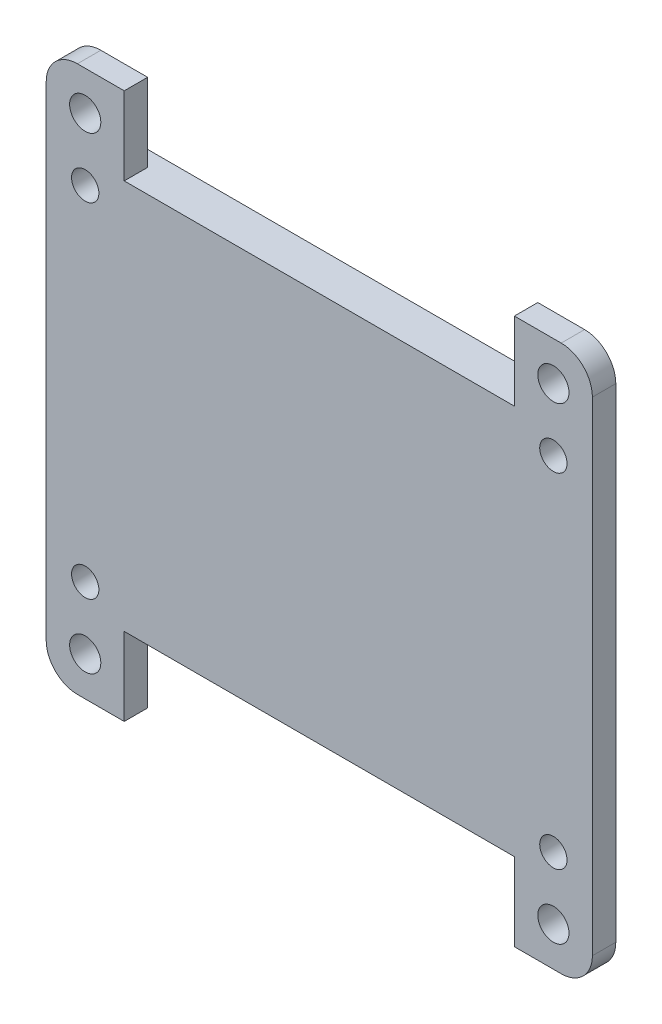
SolidWorks part; units mm, degrees
ref_plane "Front Plane" through (0, 0, 0) normal (0, 0, 1) x (1, 0, 0)
ref_plane "Top Plane" through (0, 0, 0) normal (0, 1, 0) x (1, 0, 0)
ref_plane "Right Plane" through (0, 0, 0) normal (1, 0, 0) x (0, 0, -1)
sketch "Sketch1" plane through (0, 0, 0) normal (0, 0, 1) x (1, 0, 0)
  line L0 (-45.0891, 0) -> (42.8661, 0) construction
  line L1 (-33, -25) -> (33, -25)
  line L2 (-33, -25) -> (-33, 25)
  line L3 (-33, 25) -> (33, 25)
  line L4 (33, -25) -> (33, 25)
  circle A0 centre (-30, 22) radius 1.75
  circle A1 centre (30, 22) radius 1.75
  circle A2 centre (30, -22) radius 1.75
  circle A3 centre (-30, -22) radius 1.75
  point P0 (0, 0)
  dimension "D4" = 3.5
  dimension "D1" = 66
  dimension "D2" = 50
  dimension "D3" = 60
  dimension "D5" = 22
extrude "Boss-Extrude1" add sketch "Sketch1" along normal blind 2
fillet "Fillet1" radius 3 4 edges at (-33, -25, 1) (33, -25, 1) (33, 25, 1) (-33, 25, 1)
sketch "Sketch2" plane through (0, 0, 2) normal (0, 0, 1) x (1, 0, 0)
  line L0 (-47.0426, 0) -> (59.9913, 0) construction
  line L1 (-35, -35) -> (35, -35)
  line L2 (-35, -35) -> (-35, 35)
  line L3 (-35, 35) -> (35, 35)
  line L4 (35, -35) -> (35, 35)
  line L5 (-35, -35) -> (35, 35) construction
  line L6 (-35, 35) -> (35, -35) construction
  line L8 (-25, 35) -> (25, 35)
  line L9 (-25, 35) -> (-25, 25)
  line L10 (-25, 25) -> (25, 25)
  line L11 (25, 35) -> (25, 25)
  line L12 (-25, -25) -> (25, -25)
  line L13 (-25, -25) -> (-25, -35)
  line L14 (-25, -35) -> (25, -35)
  line L15 (25, -25) -> (25, -35)
  circle A0 centre (-30, 30) radius 2
  circle A1 centre (30, 30) radius 2
  circle A2 centre (30, -30) radius 2
  circle A3 centre (-30, -30) radius 2
  circle A4 centre (-30, -22) radius 1.75 construction
  circle A5 centre (30, -22) radius 1.75 construction
  circle A6 centre (30, 22) radius 1.75 construction
  circle A7 centre (-30, 22) radius 1.75 construction
  circle A8 centre (-30, -22) radius 1.75
  circle A9 centre (30, -22) radius 1.75
  circle A10 centre (30, 22) radius 1.75
  circle A11 centre (-30, 22) radius 1.75
  point P0 (0, 0)
  line M16 (-33, 22) -> (-33, -22)
  arc M17 (-33, -22) -> (-30, -25) centre (-30, -22) ccw
  line M18 (-30, -25) -> (30, -25)
  arc M19 (30, -25) -> (33, -22) centre (30, -22) ccw
  line M20 (33, -22) -> (33, 22)
  arc M21 (33, 22) -> (30, 25) centre (30, 22) ccw
  line M22 (30, 25) -> (-30, 25)
  arc M23 (-30, 25) -> (-33, 22) centre (-30, 22) ccw
  circle M24 centre (-30, 22) radius 1.75
  circle M25 centre (30, 22) radius 1.75
  circle M26 centre (30, -22) radius 1.75
  circle M27 centre (-30, -22) radius 1.75
  dimension "D4" = 4
  dimension "D5" = 5
  dimension "D1" = 70
  dimension "D2" = 70
  dimension "D3" = 60
  dimension "D6" = 5
extrude "Boss-Extrude2" add sketch "Sketch2" along normal blind 3 contours M23 M16 M17 M18 M19 M20 M21 M22 M24 M26 M27 M25 | L13 L9 L3 L2 L1 A0 A3 M18 M17 M16 M23 M22 | L15 L1 L4 L3 L11 A1 A2 M18 M22 M21 M20 M19
fillet "Fillet2" radius 4 4 edges at (35, -35, 3.5) (-35, -35, 3.5) (-35, 35, 3.5) (35, 35, 3.5)
